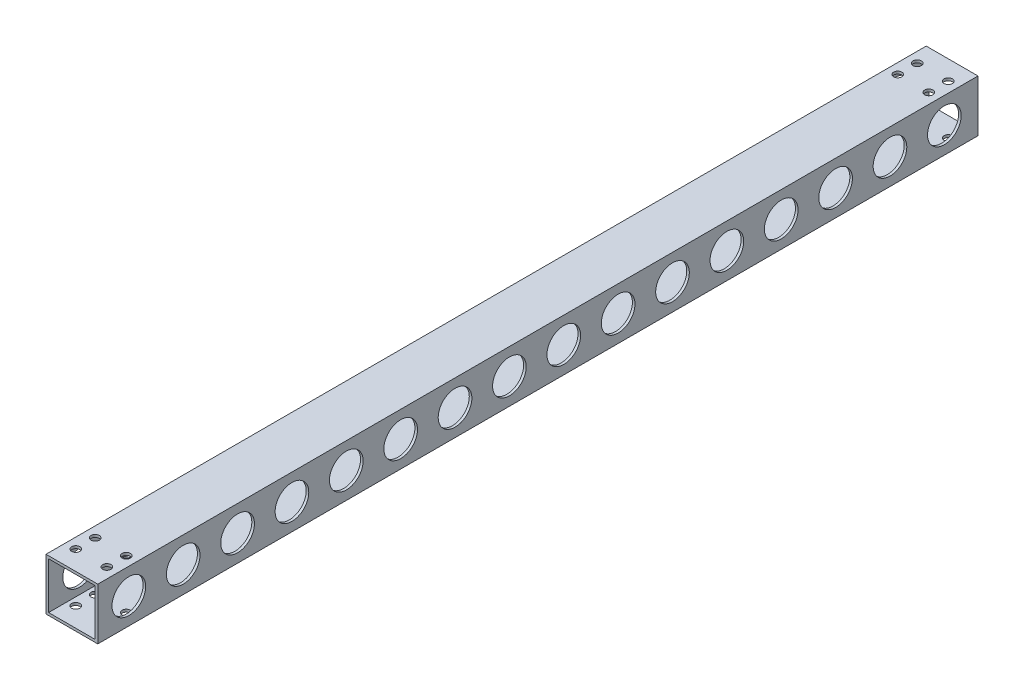
SolidWorks part; units mm, degrees
material "1100-O 棒材(SS)"
ref_plane "前视基准面" through (0, 0, 0) normal (0, 0, 1) x (1, 0, 0)
ref_plane "上视基准面" through (0, 0, 0) normal (0, 1, 0) x (1, 0, 0)
ref_plane "右视基准面" through (0, 0, 0) normal (1, 0, 0) x (0, 0, -1)
other "Configuration Table"
sketch "草图2" plane through (0, 0, 0) normal (0, 0, 1) x (1, 0, 0)
  line L1 (0, 0) -> (20, 0)
  line L2 (0, 0) -> (0, 20)
  line L3 (0, 20) -> (20, 20)
  line L4 (20, 0) -> (20, 20)
  line L5 (1, 1) -> (19, 1)
  line L6 (1, 1) -> (1, 19)
  line L7 (1, 19) -> (19, 19)
  line L8 (19, 1) -> (19, 19)
  dimension "D1" = 20
  dimension "D2" = 20
  dimension "D3" = 1
  dimension "D4" = 1
  dimension "D5" = 1
  dimension "D6" = 1
extrude "凸台-拉伸1" add sketch "草图2" along normal blind 340
sketch "草图3" plane through (0, 0, 0) normal (0, -1, 0) x (1, 0, 0)
  circle A1 centre (16, 332.5) radius 1.6
  circle A2 centre (16, 332.5) radius 1.6
  circle A3 centre (4, 332.5) radius 1.6
  circle A4 centre (4, 332.5) radius 1.6
  circle A5 centre (16, 325) radius 1.6
  circle A6 centre (16, 325) radius 1.6
  circle A7 centre (4, 325) radius 1.6
  circle A8 centre (4, 325) radius 1.6
  circle A9 centre (16, 7.5) radius 1.6
  circle A11 centre (16, 7.5) radius 1.6
  circle A13 centre (4, 7.5) radius 1.6
  circle A15 centre (4, 7.5) radius 1.6
  circle A17 centre (16, 15) radius 1.6
  circle A19 centre (16, 15) radius 1.6
  circle A21 centre (4, 15) radius 1.6
  circle A23 centre (4, 15) radius 1.6
  dimension "D1" = 0
  dimension "D2" = 0
  dimension "D3" = 0
  dimension "D4" = 0
  dimension "D5" = 0
  dimension "D6" = 0
  dimension "D7" = 0
  dimension "D8" = 0
extrude "切除-拉伸1" cut sketch "草图3" against normal through all
sketch "草图4" plane through (20, 0, 0) normal (1, 0, 0) x (0, 0, -1)
  line L0 (-340, 20) -> (0, 20) construction
  line L1 (-340, 0) -> (-340, 20) construction
  circle A0 centre (-328, 10) radius 6.5
  circle A1 centre (-307, 10) radius 6.5
  circle A2 centre (-286, 10) radius 6.5
  circle A3 centre (-265, 10) radius 6.5
  circle A4 centre (-244, 10) radius 6.5
  circle A5 centre (-223, 10) radius 6.5
  circle A6 centre (-202, 10) radius 6.5
  circle A7 centre (-181, 10) radius 6.5
  circle A8 centre (-160, 10) radius 6.5
  circle A9 centre (-139, 10) radius 6.5
  circle A10 centre (-118, 10) radius 6.5
  circle A11 centre (-97, 10) radius 6.5
  circle A12 centre (-76, 10) radius 6.5
  circle A13 centre (-55, 10) radius 6.5
  circle A14 centre (-34, 10) radius 6.5
  circle A15 centre (-13, 10) radius 6.5
  dimension "D1" = 13
  dimension "D2" = 10
  dimension "D3" = 12
  dimension "D5" = 21
  dimension "D6" = 21
  dimension "D7" = 21
  dimension "D8" = 10
  dimension "D9" = 10
  dimension "D4" = 14
extrude "切除-拉伸2" cut sketch "草图4" against normal through all
